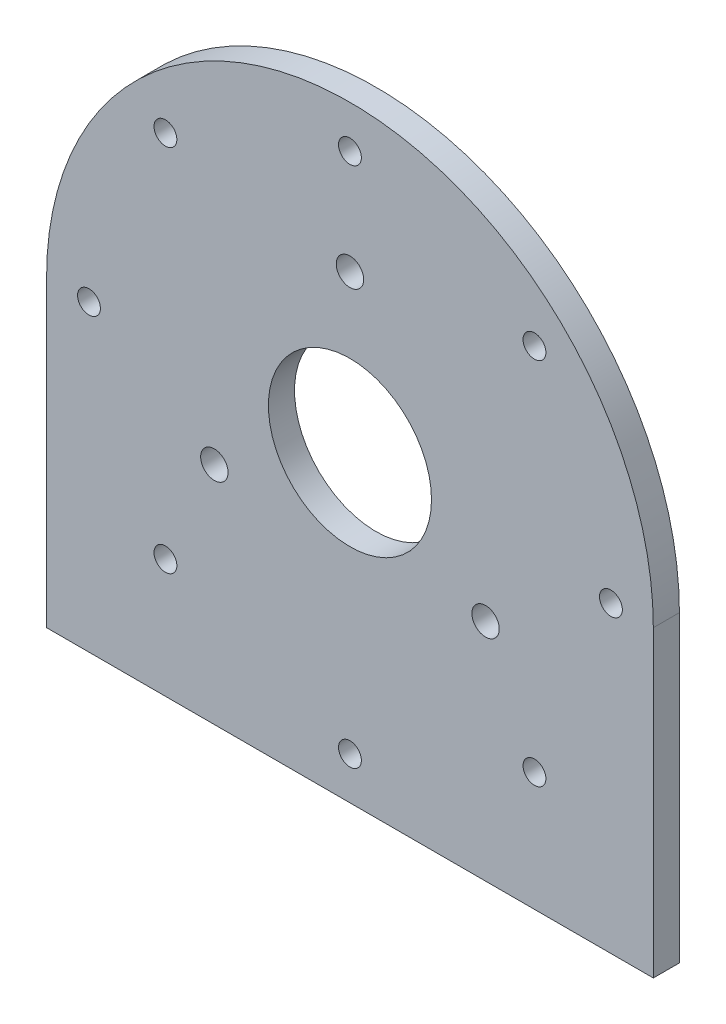
SolidWorks part; units mm, degrees
material "6061-T6 (SS)"
ref_plane "Front Plane" through (0, 0, 0) normal (0, 0, 1) x (1, 0, 0)
ref_plane "Top Plane" through (0, 0, 0) normal (0, 1, 0) x (1, 0, 0)
ref_plane "Right Plane" through (0, 0, 0) normal (1, 0, 0) x (0, 0, -1)
sketch "Sketch1" plane through (0, 0, 0) normal (0, 0, 1) x (1, 0, 0)
  line L0 (0, 0) -> (0, 24) construction
  line L1 (0, 0) -> (-20.7846, -12) construction
  line L2 (0, 0) -> (20.7846, -12) construction
  line L3 (-46.5, 0) -> (-46.5, -46.5)
  line L4 (-46.5, -46.5) -> (46.5, -46.5)
  line L5 (46.5, -46.5) -> (46.5, 0)
  line L6 (0, 0) -> (0, 40)
  circle A0 centre (0, 0) radius 46.5 construction
  circle A1 centre (0, 24) radius 2.1
  circle A2 centre (-20.7846, -12) radius 2.1
  circle A3 centre (20.7846, -12) radius 2.1
  arc A4 (-46.5, 0) -> (46.5, 0) centre (0, 0) cw
  circle A5 centre (0, 0) radius 12.5
  circle A6 centre (0, 40) radius 1.75
  circle A7 centre (28.2843, 28.2843) radius 1.75
  circle A8 centre (40, 0) radius 1.75
  circle A9 centre (28.2843, -28.2843) radius 1.75
  circle A10 centre (0, -40) radius 1.75
  circle A11 centre (-28.2843, -28.2843) radius 1.75
  circle A12 centre (-40, 0) radius 1.75
  circle A13 centre (-28.2843, 28.2843) radius 1.75
  point P32 (0, 0)
  dimension "D5" = 93
  dimension "D7" = 4.2
  dimension "D8" = 4.2
  dimension "D9" = 4.2
  dimension "D10" = 25
  dimension "D12" = 3.5
  dimension "D1" = 120
  dimension "D2" = 24
  dimension "D3" = 24
  dimension "D4" = 24
  dimension "D6" = 120
  dimension "D11" = 40
  dimension "D13" = 8
extrude "Boss-Extrude1" add sketch "Sketch1" along normal blind 4 contours A4 L3 L4 L5 A3 A2 A1
